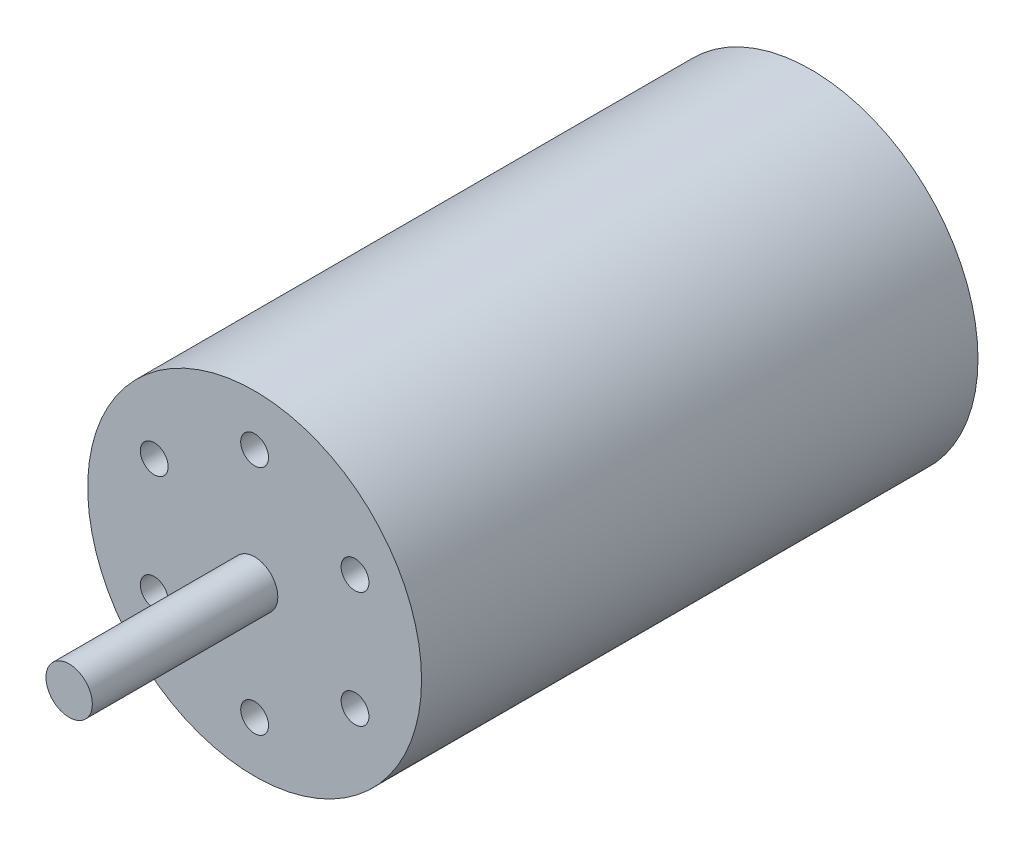
SolidWorks part; units mm, degrees
material "AISI 1020 Steel, Cold Rolled"
ref_plane "Front" through (0, 0, 0) normal (0, 0, 1) x (1, 0, 0)
ref_plane "Top" through (0, 0, 0) normal (0, 1, 0) x (1, 0, 0)
ref_plane "Right" through (0, 0, 0) normal (1, 0, 0) x (0, 0, -1)
sketch "Sketch1" plane through (0, 0, 0) normal (0, 0, 1) x (1, 0, 0)
  circle A0 centre (0, 0) radius 18
  dimension "D1" = 36
extrude "Boss-Extrude1" add sketch "Sketch1" along normal blind 60
sketch "Sketch2" plane through (0, 0, 60) normal (0, 0, 1) x (1, 0, 0)
  circle A0 centre (0, 0) radius 2.5
  dimension "D1" = 5
extrude "Boss-Extrude2" add sketch "Sketch2" along normal blind 20
sketch "Sketch3" plane through (0, 0, 60) normal (0, 0, 1) x (1, 0, 0)
  circle A0 centre (0, 0) radius 12.5 construction
  circle A1 centre (0, 12.5) radius 1.5
  circle A2 centre (10.8253, 6.25) radius 1.5
  circle A3 centre (10.8253, -6.25) radius 1.5
  circle A4 centre (0, -12.5) radius 1.5
  circle A5 centre (-10.8253, -6.25) radius 1.5
  circle A6 centre (-10.8253, 6.25) radius 1.5
  point P17 (0, 0)
  dimension "D1" = 6
extrude "Cut-Extrude1" cut sketch "Sketch3" against normal blind 10
